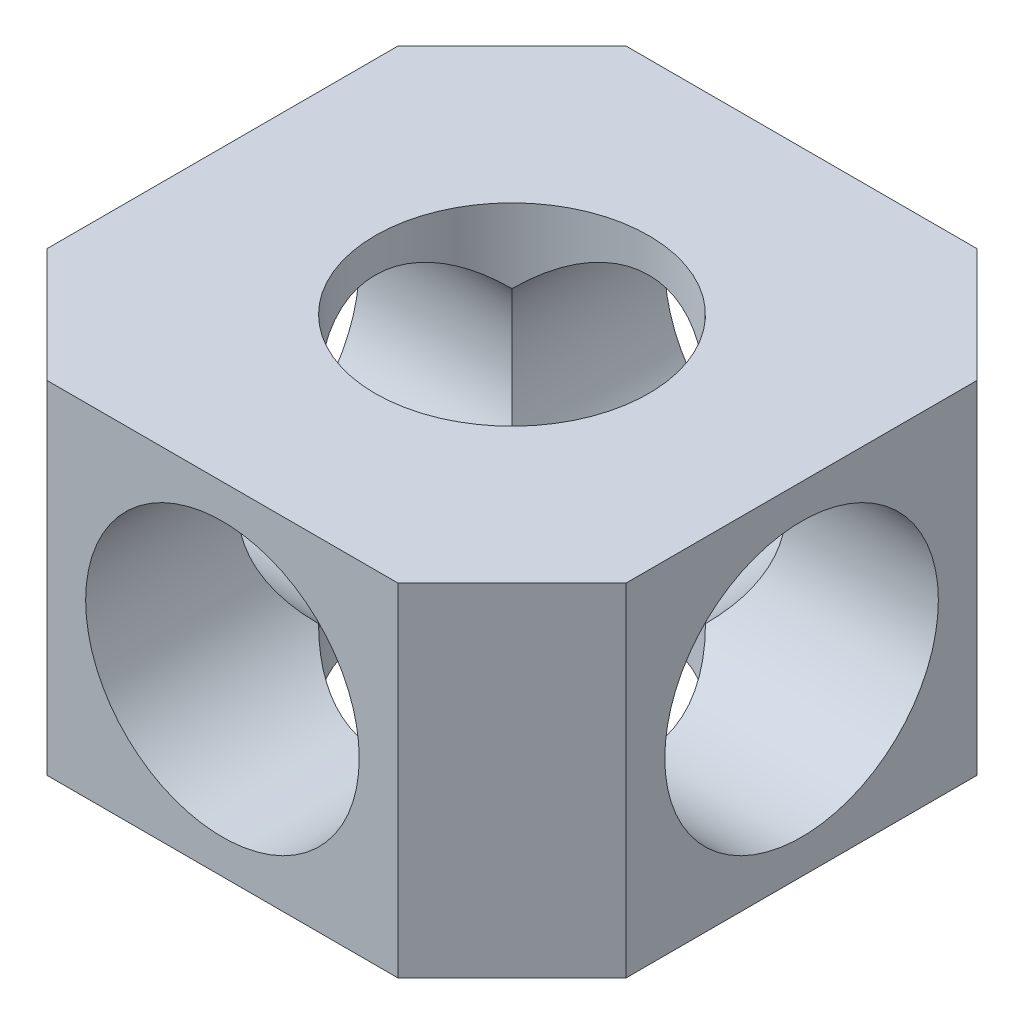
SolidWorks part; units mm, degrees
ref_plane "前视基准面" through (0, 0, 0) normal (0, 0, 1) x (1, 0, 0)
ref_plane "上视基准面" through (0, 0, 0) normal (0, 1, 0) x (1, 0, 0)
ref_plane "右视基准面" through (0, 0, 0) normal (1, 0, 0) x (0, 0, -1)
other "Configuration Table"
sketch "草图1" plane through (0, 0, 0) normal (0, 1, 0) x (1, 0, 0)
  line L1 (-12.7, -12.7) -> (12.7, -12.7)
  line L2 (-12.7, -12.7) -> (-12.7, 12.7)
  line L3 (-12.7, 12.7) -> (12.7, 12.7)
  line L4 (12.7, -12.7) -> (12.7, 12.7)
  line L5 (-12.7, -12.7) -> (12.7, 12.7) construction
  line L6 (-12.7, 12.7) -> (12.7, -12.7) construction
  point P0 (0, 0)
  dimension "D1" = 25.4
  dimension "D2" = 25.4
extrude "凸台-拉伸1" add sketch "草图1" along normal blind 15
sketch "草图2" plane through (0, 0, 0) normal (0, 1, 0) x (1, 0, 0)
  line L0 (0, -1000) -> (0, 49000) construction
  line L1 (-1000, 0) -> (49000, 0) construction
  line L2 (-12.7, 12.7) -> (-12.7, 7.7)
  line L3 (-12.7, 12.7) -> (-12.7, -12.7) construction
  line L4 (-12.7, 7.7) -> (-7.7, 12.7)
  line L5 (12.7, 12.7) -> (-12.7, 12.7) construction
  line L6 (-7.7, 12.7) -> (-12.7, 12.7)
  line L7 (12.7, 12.7) -> (12.7, 7.7)
  line L8 (7.7, 12.7) -> (12.7, 12.7)
  line L9 (12.7, 7.7) -> (7.7, 12.7)
  line L10 (12.7, -12.7) -> (12.7, -7.7)
  line L11 (7.7, -12.7) -> (12.7, -12.7)
  line L12 (12.7, -7.7) -> (7.7, -12.7)
  line L13 (-12.7, -12.7) -> (-12.7, -7.7)
  line L14 (-12.7, -7.7) -> (-7.7, -12.7)
  line L15 (-7.7, -12.7) -> (-12.7, -12.7)
  dimension "D1" = 5
  dimension "D2" = 5
extrude "切除-拉伸1" cut sketch "草图2" along normal blind 15
sketch "草图3" plane through (0, 0, 0) normal (0, 1, 0) x (1, 0, 0)
  circle A0 centre (0, 0) radius 6
  dimension "D1" = 12
extrude "切除-拉伸2" cut sketch "草图3" along normal blind 15
sketch "草图4" plane through (0, 0, 0) normal (0, 0, 1) x (1, 0, 0)
  line L0 (-7.7, 15) -> (7.7, 15) construction
  line L1 (-7.7, 15) -> (-7.7, 0) construction
  circle A0 centre (0, 7.5) radius 6
  dimension "D1" = 12
  dimension "D2" = 7.5
  dimension "D3" = 7.7
extrude "切除-拉伸3" cut sketch "草图4" against normal blind 15 and the other way blind 15
sketch "草图5" plane through (0, 0, 0) normal (1, 0, 0) x (0, 0, -1)
  line L0 (-7.7, 0) -> (7.7, 0) construction
  line L1 (-7.7, 15) -> (-7.7, 0) construction
  circle A0 centre (0, 7.5) radius 6
  dimension "D1" = 12
  dimension "D2" = 7.5
  dimension "D3" = 7.7
extrude "切除-拉伸4" cut sketch "草图5" against normal blind 15 and the other way blind 15
